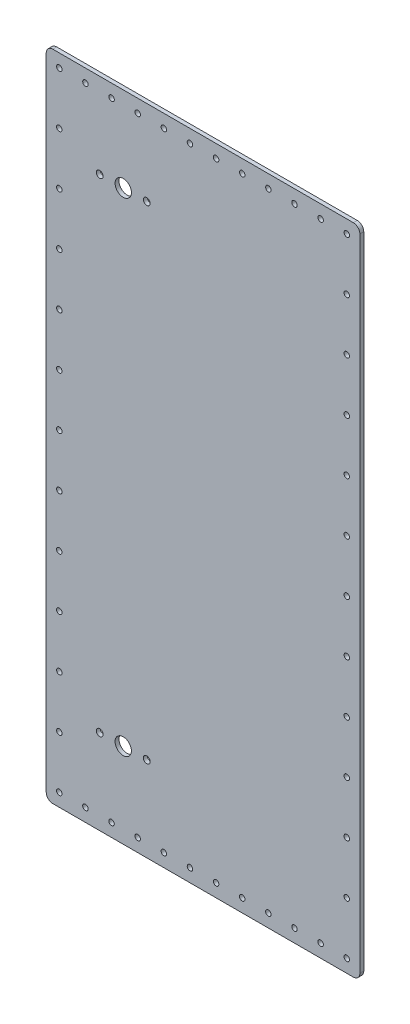
SolidWorks part; units mm, degrees
material "Thornel Mat VMA"
ref_plane "Front Plane" through (0, 0, 0) normal (0, 0, 1) x (1, 0, 0)
ref_plane "Top Plane" through (0, 0, 0) normal (0, 1, 0) x (1, 0, 0)
ref_plane "Right Plane" through (0, 0, 0) normal (1, 0, 0) x (0, 0, -1)
sketch "Sketch1" plane through (0, 0, 0) normal (0, 0, 1) x (1, 0, 0)
  line L1 (-120, -250) -> (120, -250)
  line L2 (-120, -250) -> (-120, 250)
  line L3 (-120, 250) -> (120, 250)
  line L4 (120, -250) -> (120, 250)
  line L5 (-120, -250) -> (120, 250) construction
  line L6 (-120, 250) -> (120, -250) construction
  point P0 (0, 0)
  dimension "D1" = 240
  dimension "D2" = 500
extrude "Boss-Extrude1" add sketch "Sketch1" along normal blind 3
sketch "Sketch2" plane through (0, 0, 3) normal (0, 0, 1) x (1, 0, 0)
  line L0 (0, 0) -> (-120, 0) construction
  line L1 (-120, 250) -> (-120, -250) construction
  line L2 (0, 0) -> (0, 250) construction
  line L3 (120, 250) -> (-120, 250) construction
  circle A0 centre (-110, 240) radius 2.1
  circle A4 centre (-110, 200) radius 2.1
  circle A5 centre (-110, 160) radius 2.1
  circle A6 centre (-110, 120) radius 2.1
  circle A7 centre (-110, 80) radius 2.1
  circle A8 centre (-110, 40) radius 2.1
  circle A9 centre (-110, 0) radius 2.1
  circle A10 centre (-110, -40) radius 2.1
  circle A11 centre (-110, -80) radius 2.1
  circle A12 centre (-110, -120) radius 2.1
  circle A13 centre (-110, -160) radius 2.1
  circle A14 centre (-110, -200) radius 2.1
  dimension "D2" = 4.2
  dimension "D4" = 40
  dimension "D1" = 10
  dimension "D7" = 10
  dimension "D3" = 12
extrude "Cut-Extrude1" cut sketch "Sketch2" against normal through all
sketch "Sketch3" plane through (0, 0, 0) normal (0, 0, -1) x (-1, 0, 0)
  line L0 (110, 240) -> (-120, 240) construction
  line L1 (-120, -250) -> (-120, 250) construction
  circle A0 centre (90, 240) radius 2.1
  circle A1 centre (110, 240) radius 2.1 construction
  circle A2 centre (70, 240) radius 2.1
  circle A3 centre (50, 240) radius 2.1
  circle A4 centre (30, 240) radius 2.1
  circle A5 centre (10, 240) radius 2.1
  circle A6 centre (-10, 240) radius 2.1
  circle A7 centre (-30, 240) radius 2.1
  circle A8 centre (-50, 240) radius 2.1
  circle A9 centre (-70, 240) radius 2.1
  circle A10 centre (-90, 240) radius 2.1
  circle A11 centre (-110, 240) radius 2.1
  dimension "D1" = 4.2
  dimension "D2" = 20
  dimension "D4" = 20
  dimension "D3" = 11
extrude "Cut-Extrude2" cut sketch "Sketch3" against normal through all
mirror "Mirror1" about plane through (0, 0, 0) normal (1, 0, 0) of "Cut-Extrude1"
mirror "Mirror2" about plane through (0, 0, 0) normal (0, 1, 0) of "Cut-Extrude1", "Cut-Extrude2"
sketch "Sketch4" plane through (0, 0, 3) normal (0, 0, 1) x (1, 0, 0)
  line L0 (0, 0) -> (120, 0) construction
  line L1 (120, -250) -> (120, 250) construction
  circle A0 centre (-43.0699, -185) radius 2.6
  circle A1 centre (-79.0699, -185) radius 2.6
  circle A2 centre (-61.0699, -185) radius 6.25
  circle A3 centre (-61.0699, 185) radius 6.25
  circle A4 centre (-79.0699, 185) radius 2.6
  circle A5 centre (-43.0699, 185) radius 2.6
  dimension "D1" = 5.2
  dimension "D2" = 12.5
extrude "Cut-Extrude3" cut sketch "Sketch4" against normal through all
fillet "Fillet1" radius 5 4 edges at (120, -250, 1.5) (-120, -250, 1.5) (120, 250, 1.5) (-120, 250, 1.5)
